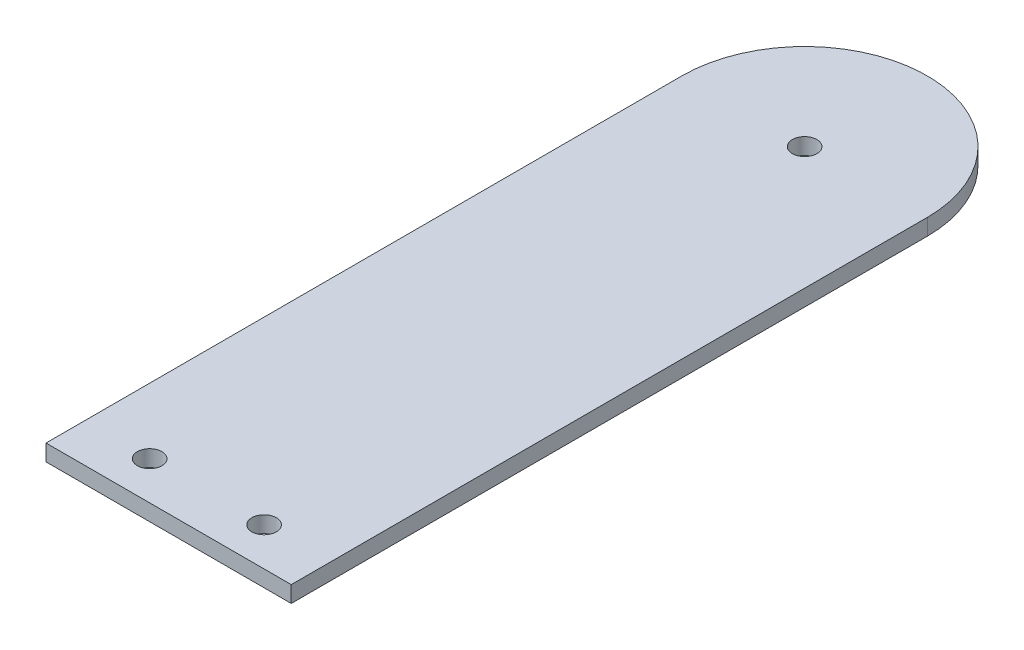
SolidWorks part; units mm, degrees
ref_plane "Спереди" through (0, 0, 0) normal (0, 0, 1) x (1, 0, 0)
ref_plane "Сверху" through (0, 0, 0) normal (0, 1, 0) x (1, 0, 0)
ref_plane "Справа" through (0, 0, 0) normal (1, 0, 0) x (0, 0, -1)
sketch "Эскиз1" plane through (0, 0, 0) normal (0, 1, 0) x (1, 0, 0)
  line L0 (-17.6252, -24.9379) -> (12.3748, -24.9379) construction
  line L1 (-17.6252, -29.6173) -> (12.3748, -29.6173)
  line L2 (-17.6252, -29.6173) -> (-17.6252, 48.1827)
  line L3 (-17.6252, 52.3827) -> (12.3748, 52.3827) construction
  line L4 (12.3748, -29.6173) -> (12.3748, 48.1827)
  line L5 (-9.6252, -26.4379) -> (4.3748, -26.4379) construction
  line L6 (-2.6252, -29.6173) -> (-2.6252, 60.301) construction
  circle A0 centre (-9.6252, -24.9379) radius 1.5
  circle A1 centre (4.3748, -24.9379) radius 1.5
  circle A2 centre (-2.6252, 48.1827) radius 1.5
  arc A4 (12.3748, 48.1827) -> (-17.6252, 48.1827) centre (-2.6252, 48.1827) ccw
  dimension "D3" = 77.8
  dimension "D4" = 3
  dimension "D7" = 3
  dimension "D2" = 30
  dimension "D5" = 14
  dimension "D6" = 8
extrude "Бобышка-Вытянуть1" add sketch "Эскиз1" along normal blind 2
